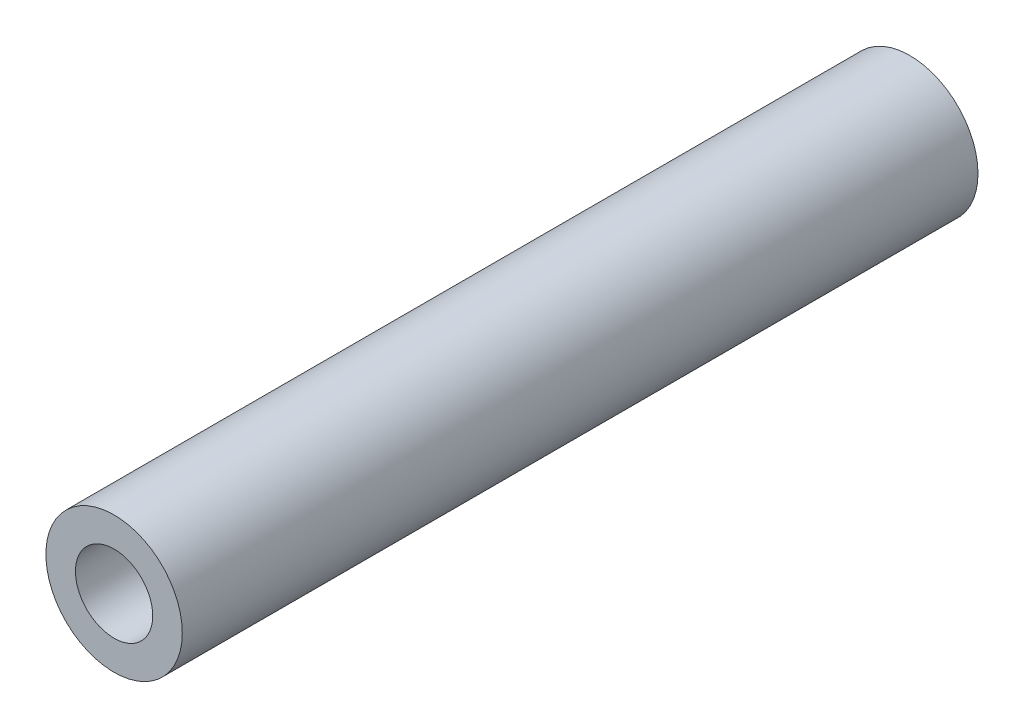
SolidWorks part; units mm, degrees
ref_plane "Front Plane" through (0, 0, 0) normal (0, 0, 1) x (1, 0, 0)
ref_plane "Top Plane" through (0, 0, 0) normal (0, 1, 0) x (1, 0, 0)
ref_plane "Right Plane" through (0, 0, 0) normal (1, 0, 0) x (0, 0, -1)
sketch "Sketch1" plane through (0, 0, 0) normal (0, 0, 1) x (1, 0, 0)
  circle A0 centre (0, 0) radius 3
  circle A1 centre (0, 0) radius 1.7
extrude "Ring_Envelope" add sketch "Sketch1" along normal blind 35
